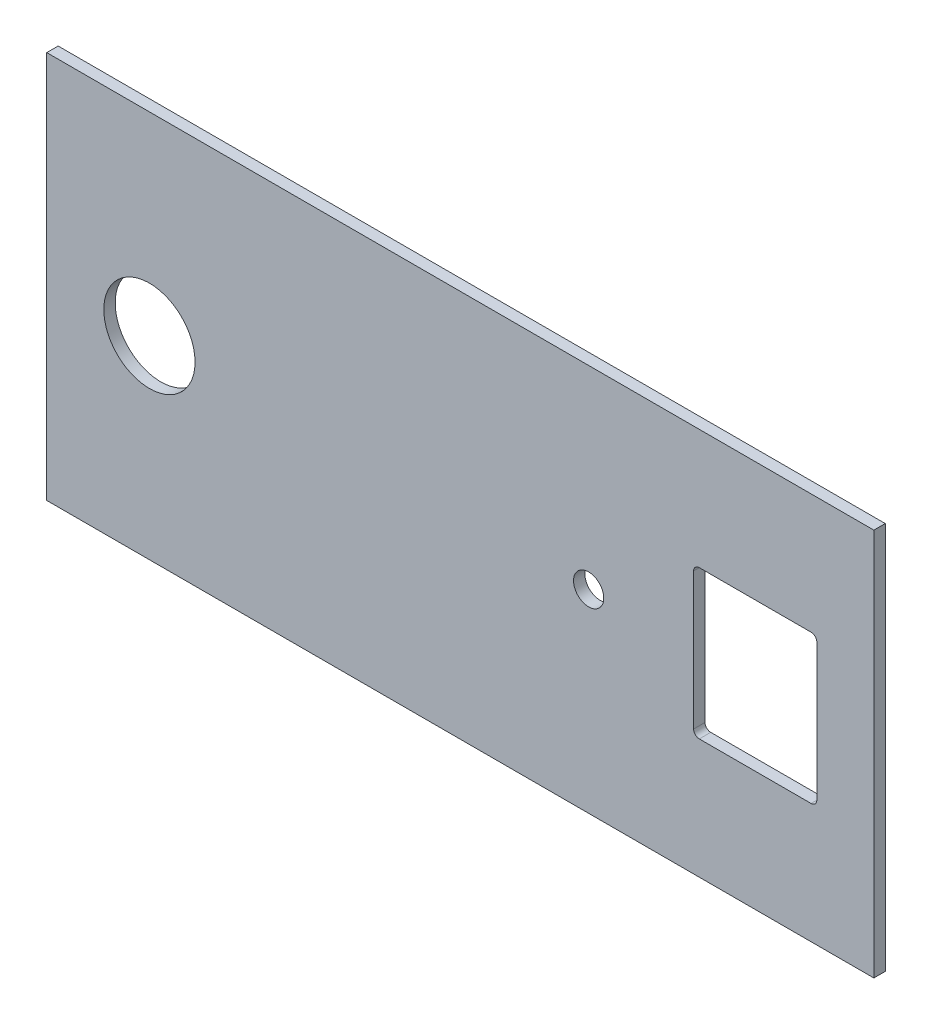
SolidWorks part; units mm, degrees
ref_plane "Front Plane" through (0, 0, 0) normal (0, 0, 1) x (1, 0, 0)
ref_plane "Top Plane" through (0, 0, 0) normal (0, 1, 0) x (1, 0, 0)
ref_plane "Right Plane" through (0, 0, 0) normal (1, 0, 0) x (0, 0, -1)
sketch "Sketch1" plane through (0, 0, 0) normal (0, 0, 1) x (1, 0, 0)
  line L1 (72.5, -34) -> (-72.5, -34)
  line L2 (72.5, -34) -> (72.5, 34)
  line L3 (72.5, 34) -> (-72.5, 34)
  line L4 (-72.5, -34) -> (-72.5, 34)
  line L5 (72.5, -34) -> (-72.5, 34) construction
  line L6 (72.5, 34) -> (-72.5, -34) construction
  point P0 (0, 0)
  dimension "D1" = 145
  dimension "D2" = 68
extrude "Boss-Extrude1" add sketch "Sketch1" along normal blind 2
sketch "Sketch2" plane through (0, 0, 2) normal (0, 0, 1) x (1, 0, 0)
  line L0 (51.7, -1006.9584) -> (51.7, 48993.0416) construction
  line L1 (-54.5, -1008.4602) -> (-54.5, 48991.5398) construction
  line L2 (-72.5, 34) -> (-72.5, -34) construction
  line L3 (72.5, -34) -> (72.5, 34) construction
  line L4 (-217.5, 0) -> (72.5, 0) construction
  line L6 (61.5, -13) -> (41.9, -13)
  line L7 (62.5, -12) -> (62.5, 12)
  line L8 (61.5, 13) -> (41.9, 13)
  line L9 (40.9, -12) -> (40.9, 12)
  line L10 (62.5, -13) -> (40.9, 13) construction
  line L11 (62.5, 13) -> (40.9, -13) construction
  arc A0 (62.5, 12) -> (61.5, 13) centre (61.5, 12) ccw
  arc A1 (61.5, -13) -> (62.5, -12) centre (61.5, -12) ccw
  arc A2 (41.9, -13) -> (40.9, -12) centre (41.9, -12) cw
  arc A3 (41.9, 13) -> (40.9, 12) centre (41.9, 12) ccw
  circle A6 centre (-54.5, 0) radius 8
  circle A7 centre (22.5, 0) radius 2.65
  point P8 (51.7, 0)
  point P11 (-72.5, 0)
  dimension "D5" = 1
  dimension "D6" = 1
  dimension "D7" = 16
  dimension "D8" = 5.3
  dimension "D9" = 50
  dimension "D1" = 18
  dimension "D2" = 20.8
  dimension "D3" = 21.6
  dimension "D4" = 26
extrude "Cut-Extrude1" cut sketch "Sketch2" against normal through all
